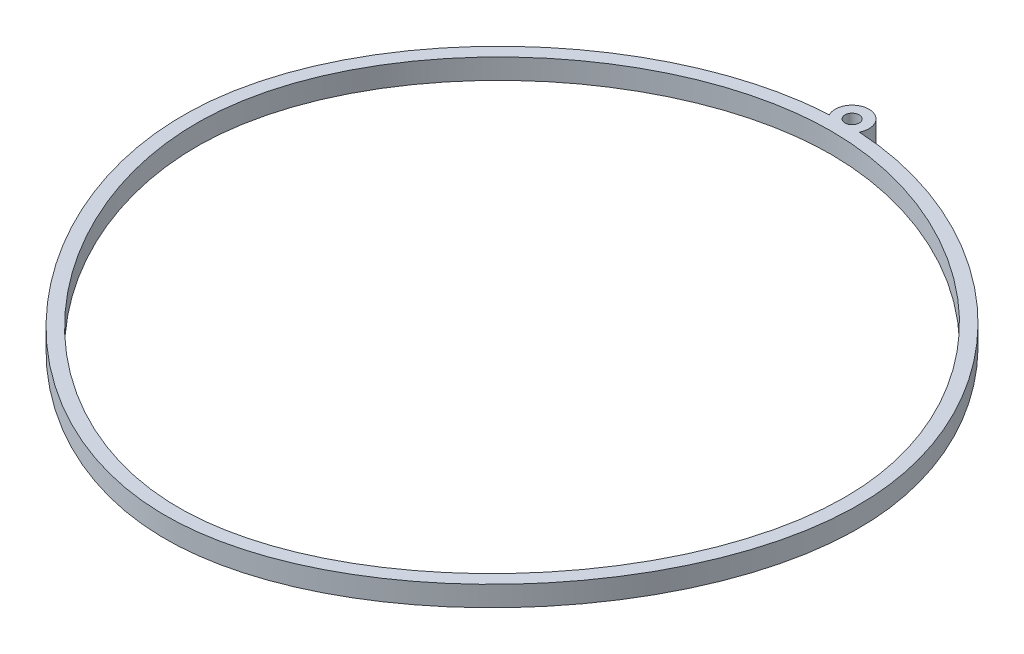
SolidWorks part; units mm, degrees
ref_plane "Front Plane" through (0, 0, 0) normal (0, 0, 1) x (1, 0, 0)
ref_plane "Top Plane" through (0, 0, 0) normal (0, 1, 0) x (1, 0, 0)
ref_plane "Right Plane" through (0, 0, 0) normal (1, 0, 0) x (0, 0, -1)
sketch "Sketch1" plane through (0, 0, 0) normal (0, 1, 0) x (1, 0, 0)
  line L0 (0, 43.4304) -> (0, -53.0816) construction
  line L1 (-47.857, 0) -> (47.857, 0) construction
  line L2 (0, 45.4304) -> (0, -55.0816) construction
  line L3 (-49.857, 0) -> (49.857, 0) construction
  circle A0 centre (0, 46.5304) radius 1.05
  arc A1 (2.2146, 45.3704) -> (-2.2146, 45.3704) centre (0, 46.5304) ccw
  spline S0 degree 3 poles (-71.9473, -0.0157) (0, 64.061) (71.9473, -0.0157) (0, -80.9488) (-71.9473, -0.0157) (0, 64.061) (71.9473, -0.0157) knots -0.762572 -0.5 -0.237428 0 0.237428 0.5 0.762572 1 1.237428 1.5 1.762572 only from (0, 43.4304) to (0, 43.4304)
  spline S1 degree 3 poles (-74.9408, -0.016) (0, 67.0565) (74.9408, -0.016) (0, -83.9437) (-74.9408, -0.016) (0, 67.0565) (74.9408, -0.016) knots -0.76207 -0.5 -0.23793 0 0.23793 0.5 0.76207 1 1.23793 1.5 1.76207 only from (0, 45.4304) to (0, 45.4304)
  dimension "D9" = 2.1
  dimension "D10" = 5
  dimension "D1" = 96.512
  dimension "D2" = 95.714
  dimension "D3" = 43.4304
  dimension "D4" = 47.857
  dimension "D5" = 100.512
  dimension "D6" = 2
  dimension "D7" = 99.714
  dimension "D8" = 2
  dimension "D11" = 3.1
extrude "Boss-Extrude1" add sketch "Sketch1" along normal blind 3 contours A1 S1 A0 | S1 S0
equation "\"D7@Sketch1\"=\"D2@Sketch1\"+4"
equation "\"D5@Sketch1\"=\"D1@Sketch1\"+4"
equation "\"D3@Sketch1\"=\"D1@Sketch1\"*0.45"
equation "\"D4@Sketch1\"=\"D2@Sketch1\"*0.5"
